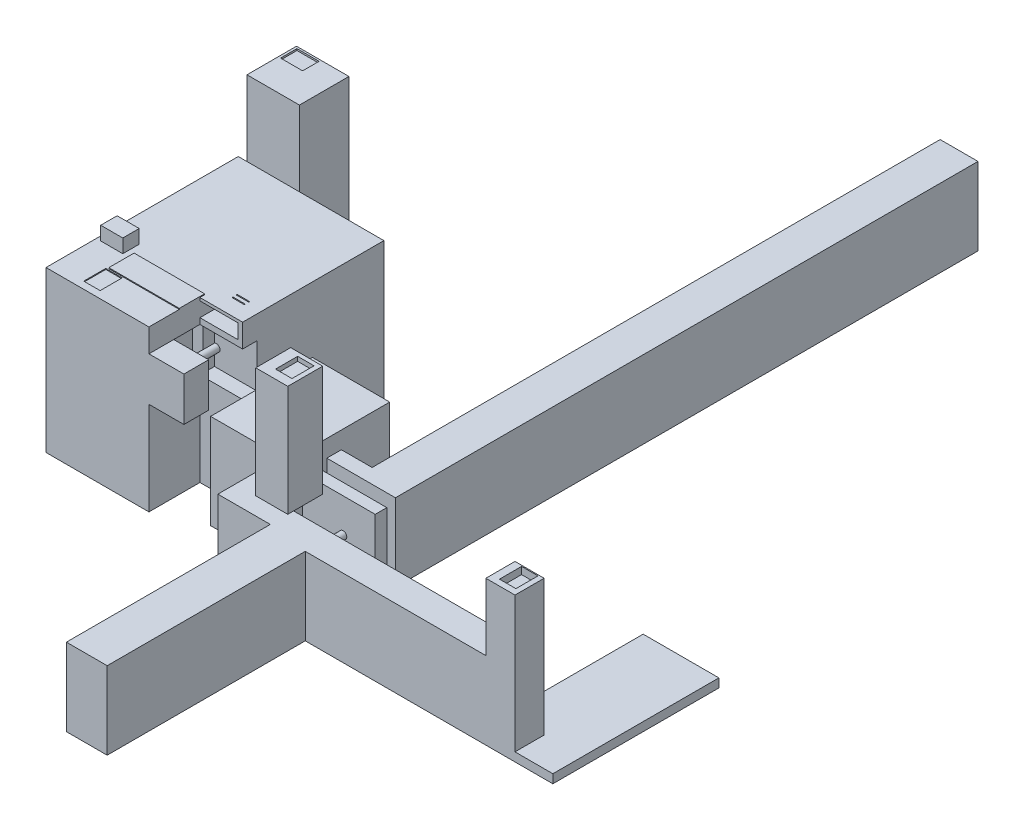
SolidWorks part; units mm, degrees
ref_plane "Front Plane" through (0, 0, 0) normal (0, 0, 1) x (1, 0, 0)
ref_plane "Top Plane" through (0, 0, 0) normal (0, 1, 0) x (1, 0, 0)
ref_plane "Right Plane" through (0, 0, 0) normal (1, 0, 0) x (0, 0, -1)
sketch "Sketch1" plane through (0, 0, 0) normal (0, 1, 0) x (1, 0, 0)
  line L1 (-250, -250) -> (250, -250)
  line L2 (-250, -250) -> (-250, 250)
  line L3 (-250, 250) -> (250, 250)
  line L4 (250, -250) -> (250, 250)
  line L5 (-250, -250) -> (250, 250) construction
  line L6 (-250, 250) -> (250, -250) construction
  point P1 (0, 0)
  dimension "D1" = 500
  dimension "D2" = 500
extrude "Boss-Extrude1" add sketch "Sketch1" along normal blind 550
sketch "Sketch2" plane through (0, 550, 0) normal (0, 1, 0) x (1, 0, 0)
  line L0 (-250, -250) -> (250, -250) construction
  line L1 (-235, -180.8) -> (-159.2, -180.8)
  line L2 (-235, -180.8) -> (-235, -237.2)
  line L3 (-235, -237.2) -> (-159.2, -237.2)
  line L4 (-159.2, -180.8) -> (-159.2, -237.2)
  line L5 (-235, -180.8) -> (-159.2, -237.2) construction
  line L6 (-235, -237.2) -> (-159.2, -180.8) construction
  line L7 (-250, 250) -> (-250, -250) construction
  point P0 (-197.1, -209)
  dimension "D1" = 12.8
  dimension "D2" = 56.4
  dimension "D3" = 15
  dimension "D4" = 75.8
extrude "Boss-Extrude2" add sketch "Sketch2" along normal blind 46.8
ref_plane "Plane1" through (0, 0, 211.7) normal (0, 0, 1) x (1, 0, 0)
ref_plane "Plane2" through (-138.6, 0, 0) normal (1, 0, 0) x (0, 0, -1)
sketch "Sketch5" plane through (-138.6, 0, 0) normal (1, 0, 0) x (0, 0, -1)
  line L5 (-250, 550) -> (-219, 550)
  line L6 (-250, 550) -> (-250, 553.15)
  line L7 (-250, 553.15) -> (-219, 553.15)
  line L8 (-219, 550) -> (-219, 553.15)
  dimension "D1" = 3.15
  dimension "D2" = 31
extrude "Boss-Extrude4" add sketch "Sketch5" along normal blind 242
sketch "Sketch6" plane through (0, 550, 0) normal (0, 1, 0) x (1, 0, 0)
  line L0 (250, -250) -> (250, 250) construction
  line L1 (103.4, -250) -> (250, -250)
  line L2 (103.4, -250) -> (103.4, -235)
  line L3 (103.4, -235) -> (250, -235)
  line L4 (250, -250) -> (250, -235)
  dimension "D1" = 15
extrude "Cut-Extrude2" cut sketch "Sketch6" against normal through all
sketch "Sketch7" plane through (0, 0, 250) normal (0, 0, 1) x (1, 0, 0)
  line L1 (-250, 550) -> (103.4, 550)
  line L2 (-250, 550) -> (-250, 0)
  line L3 (-250, 0) -> (103.4, 0)
  line L4 (103.4, 550) -> (103.4, 0)
extrude "Boss-Extrude5" add sketch "Sketch7" along normal blind 160
sketch "Sketch8" plane through (0, 0, 250) normal (0, 0, 1) x (1, 0, 0)
  line L0 (-138.6, -25.74) -> (-138.6, 25.74) construction
  line L1 (103.4, 553.15) -> (-138.6, 553.15)
  line L2 (103.4, 553.15) -> (103.4, 550)
  line L3 (103.4, 550) -> (-138.6, 550)
  line L4 (-138.6, 553.15) -> (-138.6, 550)
  line L5 (103.4, 550) -> (-138.6, 550) construction
extrude "Boss-Extrude6" add sketch "Sketch8" along normal blind 55.8
sketch "Sketch9" plane through (0, 550, 0) normal (0, 1, 0) x (1, 0, 0)
  line L0 (103.4, -410) -> (-250, -410) construction
  line L1 (-144.8, -385.8) -> (-88.4, -385.8)
  line L2 (-144.8, -385.8) -> (-144.8, -310)
  line L3 (-144.8, -310) -> (-88.4, -310)
  line L4 (-88.4, -385.8) -> (-88.4, -310)
  line L5 (-250, 250) -> (-250, -410) construction
  dimension "D1" = 24.2
  dimension "D2" = 56.4
  dimension "D3" = 75.8
  dimension "D4" = 105.2
extrude "Cut-Extrude3" cut sketch "Sketch9" against normal blind 3.25
sketch "Sketch12" plane through (0, 550, 0) normal (0, 1, 0) x (1, 0, 0)
  line L0 (250, -235) -> (250, 250) construction
  line L1 (200, -176.7) -> (160, -176.7)
  line L3 (200, -180.1) -> (160, -180.1)
  line L5 (250, -235) -> (103.4, -235) construction
  arc A0 (200, -180.1) -> (200, -176.7) centre (200, -178.4) ccw
  arc A1 (160, -176.7) -> (160, -180.1) centre (160, -178.4) ccw
  dimension "D1" = 3.4
  dimension "D3" = 40
  dimension "D4" = 50
  dimension "D5" = 56.6
extrude "Cut-Extrude6" cut sketch "Sketch12" against normal blind 10
sketch "Sketch13" plane through (0, 0, 235) normal (0, 0, 1) x (1, 0, 0)
  line L0 (103.4, 0) -> (103.4, 550) construction
  line L1 (103.4, 540) -> (233.4, 540)
  line L2 (103.4, 540) -> (103.4, 490)
  line L3 (103.4, 490) -> (233.4, 490)
  line L4 (233.4, 540) -> (233.4, 490)
  line L5 (250, 550) -> (103.4, 550) construction
  dimension "D1" = 10
  dimension "D2" = 50
  dimension "D3" = 130
extrude "Cut-Extrude7" cut sketch "Sketch13" against normal blind 130
pattern_linear "LPattern1" count 2 spacing 15 along (0, 0, -1) of "Cut-Extrude6"
sketch "Sketch14" plane through (0, 0, 235) normal (0, 0, 1) x (1, 0, 0)
  line L0 (103.4, 0) -> (103.4, 490) construction
  line L1 (103.4, 320) -> (250, 320)
  line L2 (103.4, 320) -> (103.4, 470)
  line L3 (103.4, 470) -> (250, 470)
  line L4 (250, 320) -> (250, 470)
  line L5 (250, 550) -> (103.4, 550) construction
  line L6 (250, 0) -> (250, 550) construction
  dimension "D1" = 80
  dimension "D2" = 0
  dimension "D3" = 150
extrude "Cut-Extrude8" cut sketch "Sketch14" against normal blind 50
sketch "Sketch15" plane through (250, 0, 0) normal (1, 0, 0) x (0, 0, -1)
  line L0 (-235, 0) -> (-410, 0) construction
  line L5 (-345, 0) -> (5, 0)
  line L6 (-345, 0) -> (-345, 325)
  line L7 (-345, 325) -> (5, 325)
  line L8 (5, 0) -> (5, 325)
  line L9 (-235, 0) -> (-235, 320) construction
  dimension "D1" = 325
  dimension "D2" = 110
  dimension "D3" = 350
extrude "Boss-Extrude7" add sketch "Sketch15" along normal blind 265
sketch "Sketch16" plane through (515, 0, 0) normal (1, 0, 0) x (0, 0, -1)
  line L0 (-345, 0) -> (5, 0) construction
  line L1 (-211, 0) -> (-161, 0)
  line L2 (-211, 0) -> (-211, 266.2)
  line L3 (-211, 266.2) -> (-161, 266.2)
  line L4 (-161, 0) -> (-161, 266.2)
  line L5 (5, 0) -> (5, 325) construction
  dimension "D1" = 50
  dimension "D2" = 266.2
  dimension "D3" = 216
extrude "Boss-Extrude8" add sketch "Sketch16" along normal blind 235.5
sketch "Sketch17" plane through (0, 0, 161) normal (0, 0, -1) x (-1, 0, 0)
  line L12 (-750.5, 266.2) -> (-515, 266.2) construction
  line L13 (-620.5, 266.2) -> (-750.5, 266.2)
  line L14 (-620.5, 266.2) -> (-620.5, 0)
  line L15 (-620.5, 0) -> (-750.5, 0)
  line L16 (-750.5, 266.2) -> (-750.5, 0)
  line L17 (-750.5, 0) -> (-750.5, 266.2) construction
  dimension "D1" = 130
  dimension "D2" = 0
extrude "Boss-Extrude9" add sketch "Sketch17" along normal blind 1950
sketch "Sketch18" plane through (0, 0, 345) normal (0, 0, 1) x (1, 0, 0)
  line L7 (515, 0) -> (435, 0)
  line L8 (515, 0) -> (515, 266.2)
  line L9 (515, 266.2) -> (435, 266.2)
  line L10 (435, 0) -> (435, 266.2)
  dimension "D1" = 80
extrude "Boss-Extrude10" add sketch "Sketch18" along normal blind 160
sketch "Sketch19" plane through (515, 0, 0) normal (1, 0, 0) x (0, 0, -1)
  line L0 (-505, 266.2) -> (-345, 266.2) construction
  line L1 (-425, 266.2) -> (-1205, 266.2)
  line L2 (-425, 266.2) -> (-425, 0)
  line L3 (-425, 0) -> (-1205, 0)
  line L4 (-1205, 266.2) -> (-1205, 0)
  line L5 (-505, 0) -> (-505, 266.2) construction
  dimension "D1" = 700
  dimension "D2" = 80
extrude "Boss-Extrude11" add sketch "Sketch19" along normal blind 240
sketch "Sketch20" plane through (515, 0, 0) normal (-1, 0, 0) x (0, 0, 1)
  line L0 (1205, 0) -> (505, 0) construction
  line L1 (505, 266.2) -> (1205, 266.2)
  line L2 (505, 266.2) -> (505, 0)
  line L3 (505, 0) -> (1205, 0)
  line L4 (1205, 266.2) -> (1205, 0)
extrude "Cut-Extrude9" cut sketch "Sketch20" against normal blind 100
sketch "Sketch21" plane through (755, 0, 0) normal (1, 0, 0) x (0, 0, -1)
  line L0 (-1205, 0) -> (-425, 0) construction
  line L1 (-425, 266.2) -> (-525, 266.2)
  line L2 (-425, 266.2) -> (-425, 0)
  line L3 (-425, 0) -> (-525, 0)
  line L4 (-525, 266.2) -> (-525, 0)
  dimension "D1" = 100
extrude "Boss-Extrude12" add sketch "Sketch21" along normal blind 720
sketch "Sketch22" plane through (0, 266.2, 0) normal (0, 1, 0) x (1, 0, 0)
  line L0 (1475, -525) -> (755, -525) construction
  line L1 (1475, -425) -> (1375, -425)
  line L2 (1475, -425) -> (1475, -525)
  line L3 (1475, -525) -> (1375, -525)
  line L4 (1375, -425) -> (1375, -525)
  dimension "D1" = 100
extrude "Boss-Extrude14" add sketch "Sketch22" along normal blind 230
sketch "Sketch23" plane through (0, 496.2, 0) normal (0, 1, 0) x (1, 0, 0)
  line L0 (1475, -525) -> (1475, -425) construction
  line L1 (1401.1, -428.55) -> (1457.5, -428.55)
  line L2 (1401.1, -428.55) -> (1401.1, -504.35)
  line L3 (1401.1, -504.35) -> (1457.5, -504.35)
  line L4 (1457.5, -428.55) -> (1457.5, -504.35)
  line L5 (1475, -425) -> (1375, -425) construction
  dimension "D1" = 75.8
  dimension "D2" = 56.4
  dimension "D3" = 17.5
  dimension "D4" = 3.55
extrude "Cut-Extrude10" cut sketch "Sketch23" against normal blind 24.4
sketch "Sketch24" plane through (515, 0, 0) normal (1, 0, 0) x (0, 0, -1)
  line L0 (-425, 0) -> (-211, 0) construction
  line L1 (-295, 0) -> (-255, 0)
  line L2 (-295, 0) -> (-295, 266.2)
  line L3 (-295, 266.2) -> (-255, 266.2)
  line L4 (-255, 0) -> (-255, 266.2)
  line L5 (-425, 0) -> (-425, 266.2) construction
  dimension "D1" = 130
  dimension "D2" = 40
extrude "Boss-Extrude15" add sketch "Sketch24" along normal blind 250
sketch "Sketch25" plane through (0, 0, 295) normal (0, 0, 1) x (1, 0, 0)
  line L0 (435, 0) -> (615, 0) construction
  line L1 (515, 325) -> (515, 266.2) construction
  circle A0 centre (655, 150) radius 12.5
  dimension "D1" = 25
  dimension "D2" = 150
  dimension "D3" = 140
extrude "Boss-Extrude16" add sketch "Sketch25" along normal up to next
sketch "Sketch26" plane through (0, 266.2, 0) normal (0, 1, 0) x (1, 0, 0)
  line L0 (615, -505) -> (435, -505) construction
  line L1 (505, -445) -> (615, -445)
  line L2 (505, -445) -> (505, -325)
  line L3 (505, -325) -> (615, -325)
  line L4 (615, -445) -> (615, -325)
  line L5 (435, -505) -> (435, -345) construction
  dimension "D1" = 120
  dimension "D2" = 110
  dimension "D3" = 60
  dimension "D4" = 70
extrude "Boss-Extrude22" add sketch "Sketch26" along normal blind 365.6
sketch "Sketch28" plane through (0, 631.8, 0) normal (0, 1, 0) x (1, 0, 0)
  line L0 (615, -445) -> (615, -325) construction
  line L1 (542.78, -338.9) -> (599.18, -338.9)
  line L2 (542.78, -338.9) -> (542.78, -414.7)
  line L3 (542.78, -414.7) -> (599.18, -414.7)
  line L4 (599.18, -338.9) -> (599.18, -414.7)
  line L5 (505, -445) -> (615, -445) construction
  line L7 (505, -325) -> (615, -325)
  line L8 (505, -325) -> (505, -445)
  line L9 (505, -445) -> (615, -445)
  line L10 (615, -325) -> (615, -445)
  dimension "D1" = 15.82
  dimension "D2" = 30.3
  dimension "D3" = 75.8
  dimension "D4" = 56.4
extrude "Boss-Extrude23" add sketch "Sketch28" along normal blind 15
sketch "Sketch29" plane through (103.4, 0, 0) normal (1, 0, 0) x (0, 0, -1)
  line L0 (-185, 470) -> (-185, 320) construction
  line L1 (-325, 470) -> (-225, 470)
  line L2 (-325, 470) -> (-325, 320)
  line L3 (-325, 320) -> (-225, 320)
  line L4 (-225, 470) -> (-225, 320)
  line L5 (-410, 550) -> (-305.8, 550) construction
  dimension "D1" = 40
  dimension "D2" = 100
  dimension "D3" = 150
  dimension "D4" = 80
extrude "Cut-Extrude11" cut sketch "Sketch29" against normal blind 35
sketch "Sketch30" plane through (103.4, 0, 0) normal (1, 0, 0) x (0, 0, -1)
  line L0 (-410, 0) -> (-410, 550) construction
  line L1 (-325, 470) -> (-410, 470)
  line L2 (-325, 470) -> (-325, 320)
  line L3 (-325, 320) -> (-410, 320)
  line L4 (-410, 470) -> (-410, 320)
extrude "Boss-Extrude24" add sketch "Sketch30" along normal blind 120
sketch "Sketch31" plane through (0, 0, 325) normal (0, 0, -1) x (-1, 0, 0)
  line L0 (-68.4, 320) -> (-103.4, 320) construction
  line L1 (-68.4, 470) -> (-68.4, 320) construction
  circle A0 centre (-109.9, 378.75) radius 12.5
  dimension "D3" = 25
  dimension "D1" = 58.75
  dimension "D2" = 41.5
extrude "Boss-Extrude25" add sketch "Sketch31" along normal up to next
sketch "Sketch32" plane through (0, 0, 0) normal (0, -1, 0) x (1, 0, 0)
  line L5 (1475, 525) -> (755, 525) construction
  line L6 (1365, 525) -> (1585, 525)
  line L7 (1365, 525) -> (1365, -25)
  line L8 (1365, -25) -> (1585, -25)
  line L9 (1585, 525) -> (1585, -25)
  line L10 (1475, 525) -> (1475, 425) construction
  dimension "D1" = 110
  dimension "D2" = 220
  dimension "D3" = 550
extrude "Boss-Extrude26" add sketch "Sketch32" against normal blind 30
sketch "Sketch34" plane through (0, 0, -250) normal (0, 0, -1) x (-1, 0, 0)
  line L0 (-250, 0) -> (250, 0) construction
  line L1 (40, 0) -> (220, 0)
  line L2 (40, 0) -> (40, 808)
  line L3 (40, 808) -> (220, 808)
  line L4 (220, 0) -> (220, 808)
  line L5 (250, 550) -> (250, 0) construction
  dimension "D1" = 808
  dimension "D2" = 180
  dimension "D3" = 30
extrude "Boss-Extrude28" add sketch "Sketch34" along normal blind 170
sketch "Sketch35" plane through (0, 808, 0) normal (0, 1, 0) x (1, 0, 0)
  line L0 (-220, 420) -> (-40, 420) construction
  line L1 (-136.3, 413.6) -> (-212.1, 413.6)
  line L2 (-136.3, 413.6) -> (-136.3, 357.2)
  line L3 (-136.3, 357.2) -> (-212.1, 357.2)
  line L4 (-212.1, 413.6) -> (-212.1, 357.2)
  line L5 (-220, 420) -> (-220, 250) construction
  dimension "D1" = 75.8
  dimension "D2" = 56.4
  dimension "D3" = 6.4
  dimension "D4" = 7.9
extrude "Cut-Extrude12" cut sketch "Sketch35" against normal blind 5.8
sketch "Sketch36" plane through (0, 30, 0) normal (0, 1, 0) x (1, 0, 0)
  line L0 (1365, -425) -> (1365, 25)
  line L1 (1365, 25) -> (1585, 25)
  line L2 (1585, 25) -> (1585, -525)
  line L3 (1585, -525) -> (1605, -525)
  line L4 (1605, -525) -> (1605, 45)
  line L5 (1605, 45) -> (1345, 45)
  line L6 (1345, 45) -> (1345, -425)
  line L7 (1375, -425) -> (615, -425) construction
  line L8 (1345, -425) -> (1365, -425)
  dimension "D1" = 20
  dimension "D2" = 20
  dimension "D3" = 20
extrude "Boss-Extrude29" add sketch "Sketch36" against normal blind 30
